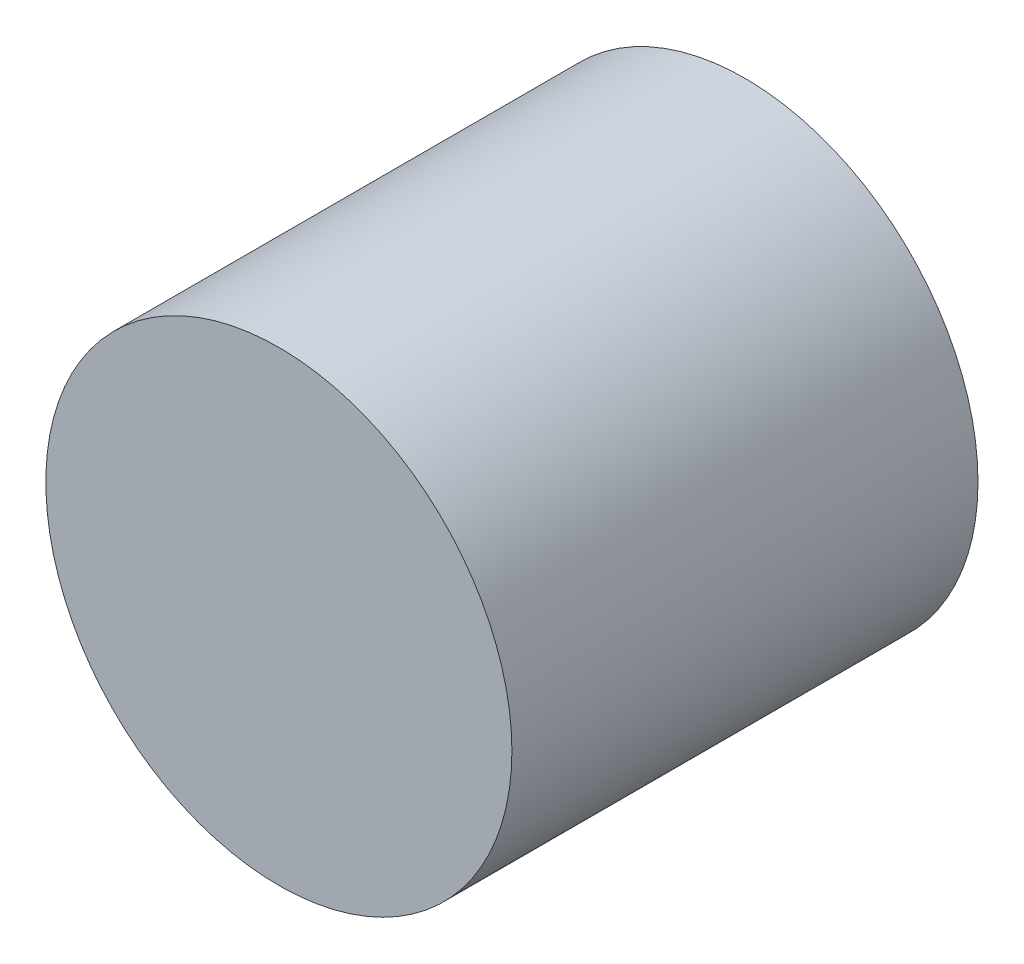
SolidWorks part; units mm, degrees
ref_plane "前视基准面" through (0, 0, 0) normal (0, 0, 1) x (1, 0, 0)
ref_plane "上视基准面" through (0, 0, 0) normal (0, 1, 0) x (1, 0, 0)
ref_plane "右视基准面" through (0, 0, 0) normal (1, 0, 0) x (0, 0, -1)
other "Configuration Table"
sketch "草图1" plane through (0, 0, 0) normal (0, 0, 1) x (1, 0, 0)
  circle A0 centre (0, 0) radius 1.5
extrude "M3x3螺钉包络" add sketch "草图1" along normal blind 3
